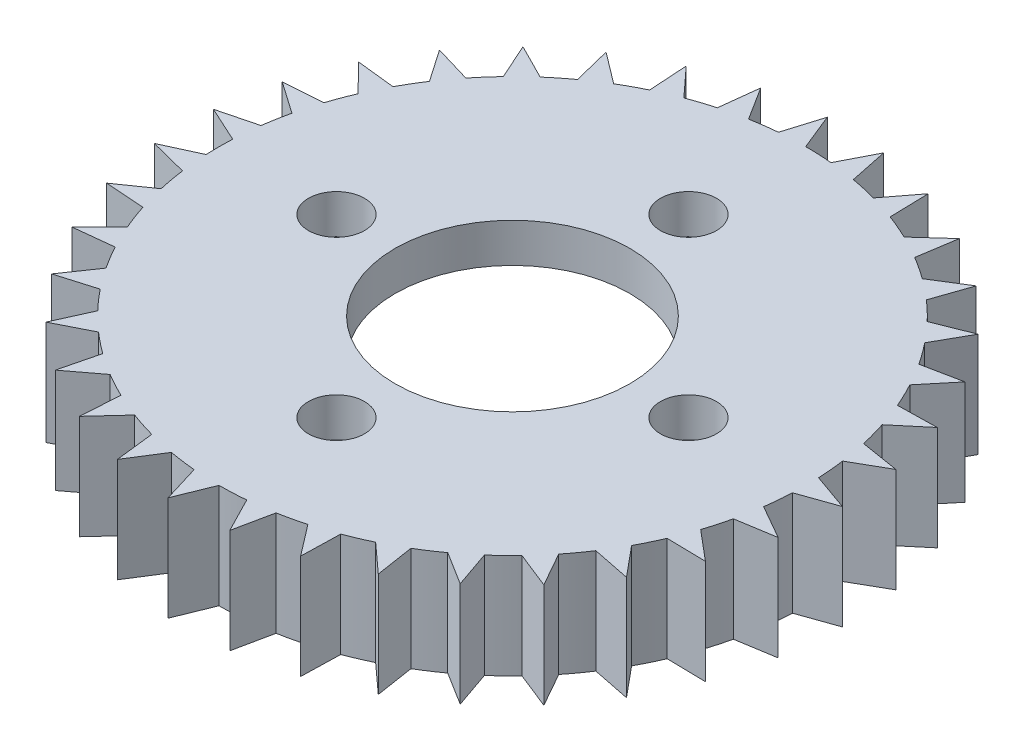
SolidWorks part; units mm, degrees
material "ABS"
ref_plane "Front Plane" through (0, 0, 0) normal (0, 0, 1) x (1, 0, 0)
ref_plane "Top Plane" through (0, 0, 0) normal (0, 1, 0) x (1, 0, 0)
ref_plane "Right Plane" through (0, 0, 0) normal (1, 0, 0) x (0, 0, -1)
sketch "Sketch1" plane through (0, 0, 0) normal (0, 1, 0) x (1, 0, 0)
  line L0 (0, 0) -> (0, -27) construction
  circle A0 centre (0, 0) radius 18
  circle A1 centre (0, 0) radius 9
  circle A2 centre (0, -13.5) radius 2.15
  circle A3 centre (-13.5, 0) radius 2.15
  circle A4 centre (0, 13.5) radius 2.15
  circle A5 centre (13.5, 0) radius 2.15
  point P16 (0, 0)
  dimension "D1" = 36
  dimension "D2" = 18
  dimension "D4" = 4.3
  dimension "D5" = 4
  dimension "D3" = 13.5
extrude "Boss-Extrude1" add sketch "Sketch1" along normal blind 3
sketch "Sketch2" plane through (0, 3, 0) normal (0, 1, 0) x (1, 0, 0)
  line L0 (0, 0) -> (44.9555, 0) construction
  line L1 (22.4778, 1) -> (25.3062, 0)
  line L2 (25.3062, 0) -> (22.4778, -1)
  line L3 (22.4778, -1) -> (22.4778, 1) construction
  line L4 (22.2951, -3.0296) -> (24.8995, -4.5186)
  line L5 (24.8995, -4.5186) -> (21.938, -4.9975)
  line L6 (21.3958, -6.9619) -> (23.6925, -8.892)
  line L7 (23.6925, -8.892) -> (20.6931, -8.8344)
  line L8 (19.8089, -10.6704) -> (21.7241, -12.9795)
  line L9 (21.7241, -12.9795) -> (18.7831, -12.3873)
  line L10 (17.5853, -14.0359) -> (19.0574, -16.6499)
  line L11 (19.0574, -16.6499) -> (16.2694, -15.5421)
  line L12 (14.7965, -16.9503) -> (15.7782, -19.7852)
  line L13 (15.7782, -19.7852) -> (13.2328, -18.1973)
  line L14 (11.5321, -19.32) -> (11.9918, -22.2845)
  line L15 (11.9918, -22.2845) -> (9.7709, -20.2677)
  line L16 (7.8971, -21.0686) -> (7.82, -24.0676)
  line L17 (7.82, -24.0676) -> (5.995, -21.6866)
  line L18 (4.0082, -22.1401) -> (3.3969, -25.0772)
  line L19 (3.3969, -25.0772) -> (2.0263, -22.4086)
  line L20 (-0.0095, -22.5) -> (-1.1354, -25.2807)
  line L21 (-1.1354, -25.2807) -> (-2.0075, -22.4103)
  line L22 (-4.0268, -22.1367) -> (-5.6312, -24.6717)
  line L23 (-5.6312, -24.6717) -> (-5.9767, -21.6917)
  line L24 (-7.9148, -21.062) -> (-9.946, -23.2697)
  line L25 (-9.946, -23.2697) -> (-9.7539, -20.2759)
  line L26 (-11.5484, -19.3102) -> (-13.9411, -21.1199)
  line L27 (-13.9411, -21.1199) -> (-13.2175, -18.2084)
  line L28 (-14.8108, -16.9379) -> (-17.4882, -18.2912)
  line L29 (-17.4882, -18.2912) -> (-16.2563, -15.5558)
  line L30 (-17.5971, -14.0211) -> (-20.4731, -14.8746)
  line L31 (-20.4731, -14.8746) -> (-18.7727, -12.4031)
  line L32 (-19.8179, -10.6537) -> (-22.8001, -10.9799)
  line L33 (-22.8001, -10.9799) -> (-20.6857, -8.8518)
  line L34 (-21.4017, -6.9439) -> (-24.3942, -6.7324)
  line L35 (-24.3942, -6.7324) -> (-21.9338, -5.016)
  line L36 (-22.2976, -3.0109) -> (-25.2043, -2.2684)
  line L37 (-25.2043, -2.2684) -> (-22.4769, -1.0189)
  line L38 (-22.4769, 1.0189) -> (-25.2043, 2.2684)
  line L39 (-25.2043, 2.2684) -> (-22.2976, 3.0109)
  line L40 (-21.9338, 5.016) -> (-24.3942, 6.7324)
  line L41 (-24.3942, 6.7324) -> (-21.4017, 6.9439)
  line L42 (-20.6857, 8.8518) -> (-22.8001, 10.9799)
  line L43 (-22.8001, 10.9799) -> (-19.8179, 10.6537)
  line L44 (-18.7727, 12.4031) -> (-20.4731, 14.8746)
  line L45 (-20.4731, 14.8746) -> (-17.5971, 14.0211)
  line L46 (-16.2563, 15.5558) -> (-17.4882, 18.2912)
  line L47 (-17.4882, 18.2912) -> (-14.8108, 16.9379)
  line L48 (-13.2175, 18.2084) -> (-13.9411, 21.1199)
  line L49 (-13.9411, 21.1199) -> (-11.5484, 19.3102)
  line L50 (-9.7539, 20.2759) -> (-9.946, 23.2697)
  line L51 (-9.946, 23.2697) -> (-7.9148, 21.062)
  line L52 (-5.9767, 21.6917) -> (-5.6312, 24.6717)
  line L53 (-5.6312, 24.6717) -> (-4.0268, 22.1367)
  line L54 (-2.0075, 22.4103) -> (-1.1354, 25.2807)
  line L55 (-1.1354, 25.2807) -> (-0.0095, 22.5)
  line L56 (2.0263, 22.4086) -> (3.3969, 25.0772)
  line L57 (3.3969, 25.0772) -> (4.0082, 22.1401)
  line L58 (5.995, 21.6866) -> (7.82, 24.0676)
  line L59 (7.82, 24.0676) -> (7.8971, 21.0686)
  line L60 (9.7709, 20.2677) -> (11.9918, 22.2845)
  line L61 (11.9918, 22.2845) -> (11.5321, 19.32)
  line L62 (13.2328, 18.1973) -> (15.7782, 19.7852)
  line L63 (15.7782, 19.7852) -> (14.7965, 16.9503)
  line L64 (16.2694, 15.5421) -> (19.0574, 16.6499)
  line L65 (19.0574, 16.6499) -> (17.5853, 14.0359)
  line L66 (18.7831, 12.3873) -> (21.7241, 12.9795)
  line L67 (21.7241, 12.9795) -> (19.8089, 10.6704)
  line L68 (20.6931, 8.8344) -> (23.6925, 8.892)
  line L69 (23.6925, 8.892) -> (21.3958, 6.9619)
  line L70 (21.938, 4.9975) -> (24.8995, 4.5186)
  line L71 (24.8995, 4.5186) -> (22.2951, 3.0296)
  circle A0 centre (0, 0) radius 18 construction
  circle A1 centre (0, 0) radius 18
  arc A2 (22.4778, 1) -> (22.2951, 3.0296) centre (0, 0) ccw
  arc A3 (22.2951, -3.0296) -> (22.4778, -1) centre (0, 0) ccw
  arc A4 (21.3958, -6.9619) -> (21.938, -4.9975) centre (0, 0) ccw
  arc A5 (19.8089, -10.6704) -> (20.6931, -8.8344) centre (0, 0) ccw
  arc A6 (17.5853, -14.0359) -> (18.7831, -12.3873) centre (0, 0) ccw
  arc A7 (14.7965, -16.9503) -> (16.2694, -15.5421) centre (0, 0) ccw
  arc A8 (11.5321, -19.32) -> (13.2328, -18.1973) centre (0, 0) ccw
  arc A9 (7.8971, -21.0686) -> (9.7709, -20.2677) centre (0, 0) ccw
  arc A10 (4.0082, -22.1401) -> (5.995, -21.6866) centre (0, 0) ccw
  arc A11 (-0.0095, -22.5) -> (2.0263, -22.4086) centre (0, 0) ccw
  arc A12 (-4.0268, -22.1367) -> (-2.0075, -22.4103) centre (0, 0) ccw
  arc A13 (-7.9148, -21.062) -> (-5.9767, -21.6917) centre (0, 0) ccw
  arc A14 (-11.5484, -19.3102) -> (-9.7539, -20.2759) centre (0, 0) ccw
  arc A15 (-14.8108, -16.9379) -> (-13.2175, -18.2084) centre (0, 0) ccw
  arc A16 (-17.5971, -14.0211) -> (-16.2563, -15.5558) centre (0, 0) ccw
  arc A17 (-19.8179, -10.6537) -> (-18.7727, -12.4031) centre (0, 0) ccw
  arc A18 (-21.4017, -6.9439) -> (-20.6857, -8.8518) centre (0, 0) ccw
  arc A19 (-22.2976, -3.0109) -> (-21.9338, -5.016) centre (0, 0) ccw
  arc A20 (-22.4769, 1.0189) -> (-22.4769, -1.0189) centre (0, 0) ccw
  arc A21 (-21.9338, 5.016) -> (-22.2976, 3.0109) centre (0, 0) ccw
  arc A22 (-20.6857, 8.8518) -> (-21.4017, 6.9439) centre (0, 0) ccw
  arc A23 (-18.7727, 12.4031) -> (-19.8179, 10.6537) centre (0, 0) ccw
  arc A24 (-16.2563, 15.5558) -> (-17.5971, 14.0211) centre (0, 0) ccw
  arc A25 (-13.2175, 18.2084) -> (-14.8108, 16.9379) centre (0, 0) ccw
  arc A26 (-9.7539, 20.2759) -> (-11.5484, 19.3102) centre (0, 0) ccw
  arc A27 (-5.9767, 21.6917) -> (-7.9148, 21.062) centre (0, 0) ccw
  arc A28 (-2.0075, 22.4103) -> (-4.0268, 22.1367) centre (0, 0) ccw
  arc A29 (2.0263, 22.4086) -> (-0.0095, 22.5) centre (0, 0) ccw
  arc A30 (5.995, 21.6866) -> (4.0082, 22.1401) centre (0, 0) ccw
  arc A31 (9.7709, 20.2677) -> (7.8971, 21.0686) centre (0, 0) ccw
  arc A32 (16.2694, 15.5421) -> (14.7965, 16.9503) centre (0, 0) ccw
  arc A33 (18.7831, 12.3873) -> (17.5853, 14.0359) centre (0, 0) ccw
  arc A34 (20.6931, 8.8344) -> (19.8089, 10.6704) centre (0, 0) ccw
  arc A35 (21.938, 4.9975) -> (21.3958, 6.9619) centre (0, 0) ccw
  arc A36 (13.2328, 18.1973) -> (11.5321, 19.32) centre (0, 0) ccw
  point P6 (22.4778, 0)
  point P114 (0, 0)
  dimension "D1" = 45
  dimension "D2" = 3
  dimension "D3" = 2
  dimension "D4" = 35
extrude "Boss-Extrude2" add sketch "Sketch2" against normal blind 8
